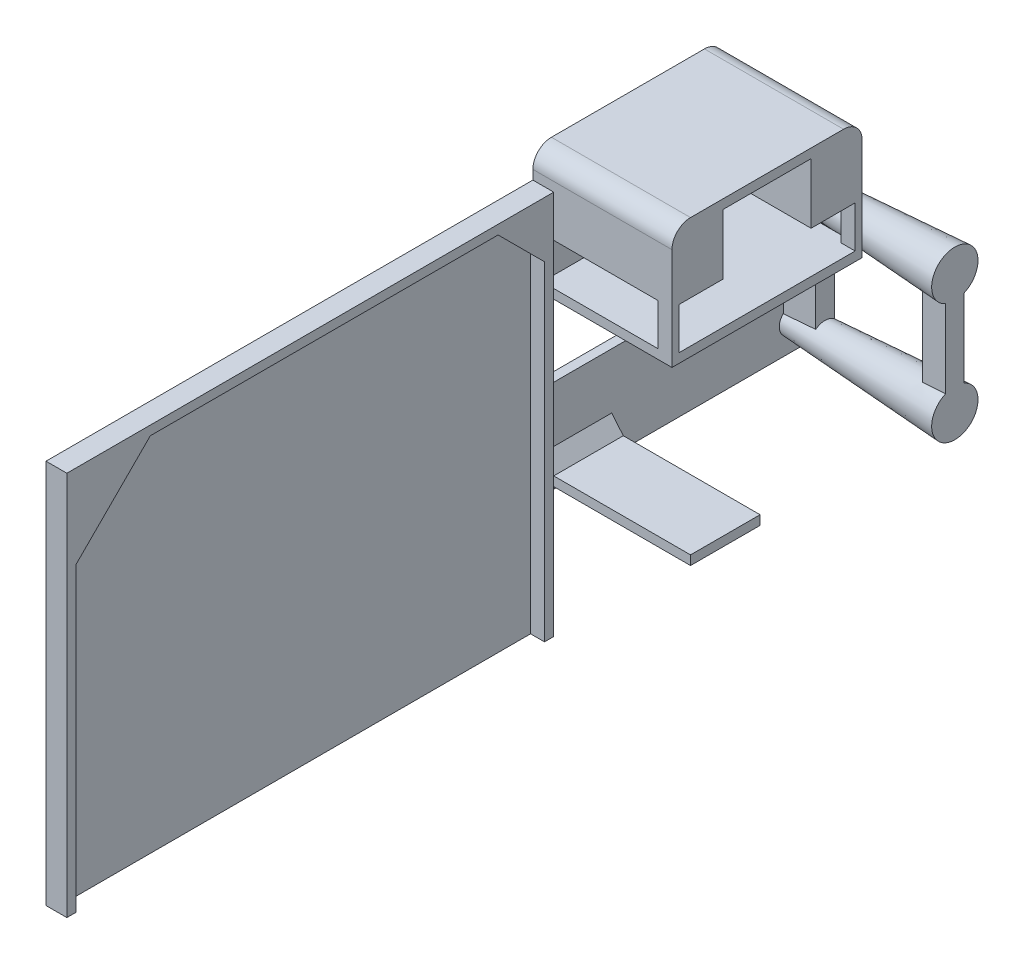
SolidWorks part; units mm, degrees
ref_plane "Front Plane" through (0, 0, 0) normal (0, 0, 1) x (1, 0, 0)
ref_plane "Top Plane" through (0, 0, 0) normal (0, 1, 0) x (1, 0, 0)
ref_plane "Right Plane" through (0, 0, 0) normal (1, 0, 0) x (0, 0, -1)
sketch "Sketch6" plane through (0, 0, 0) normal (1, 0, 0) x (0, 0, -1)
  line L1 (0, 0) -> (105, 0)
  line L2 (0, 0) -> (0, -83)
  line L3 (0, -83) -> (105, -83)
  line L4 (105, 0) -> (105, -83)
  dimension "D1" = 105
  dimension "D2" = 83
extrude "Boss-Extrude3" add sketch "Sketch6" along normal blind 4.5
sketch "Sketch9" plane through (0, -83, 0) normal (0, -1, 0) x (1, 0, 0)
  line L0 (4.5, 0) -> (4.5, -105) construction
  line L1 (0, 0) -> (0, -105) construction
  line L2 (4.5, -2) -> (1.5, -2)
  line L3 (4.5, -2) -> (4.5, -103)
  line L4 (4.5, -103) -> (1.5, -103)
  line L5 (1.5, -2) -> (1.5, -103)
  line L6 (4.5, 0) -> (0, 0) construction
  line L7 (4.5, -105) -> (0, -105) construction
  dimension "D1" = 1.5
  dimension "D2" = 2
  dimension "D3" = 2
extrude "Cut-Extrude6" cut sketch "Sketch9" against normal blind 81
sketch "Sketch10" plane through (0, 0, -2) normal (0, 0, -1) x (-1, 0, 0)
  line L1 (-4.5, -2) -> (-3.5, -2)
  line L2 (-4.5, -2) -> (-4.5, -10)
  line L3 (-4.5, -10) -> (-3.5, -10)
  line L4 (-3.5, -2) -> (-3.5, -10)
  dimension "D1" = 1
  dimension "D2" = 8
extrude "Boss-Extrude4" add sketch "Sketch10" along normal blind 8
sketch "Sketch11" plane through (0, 0, -103) normal (0, 0, 1) x (1, 0, 0)
  line L1 (4.5, -2) -> (3.2738, -2)
  line L2 (4.5, -2) -> (4.5, -7)
  line L3 (4.5, -7) -> (3.2738, -7)
  line L4 (3.2738, -2) -> (3.2738, -7)
  dimension "D1" = 5
extrude "Boss-Extrude5" add sketch "Sketch11" along normal blind 5
sketch "Sketch18" plane through (4.5, 0, 0) normal (1, 0, 0) x (0, 0, -1)
  line L0 (103, -12) -> (93, -2)
  line L1 (103, -7) -> (103, -83) construction
  line L2 (98, -2) -> (10, -2) construction
  line L3 (103, -12) -> (103, -2)
  line L4 (103, -2) -> (93, -2)
  line L5 (18, -2) -> (2, -2)
  line L6 (2, -2) -> (2, -18)
  line L7 (2, -10) -> (2, -83) construction
  line L8 (2, -18) -> (18, -2)
  dimension "D1" = 0
  dimension "D2" = 10
  dimension "D3" = 0
  dimension "D4" = 16
  dimension "D5" = 22.6274
extrude "Boss-Extrude12" add sketch "Sketch18" against normal up to vertex (1.2262 mm away)
sketch "Sketch27" plane through (0, 0, 0) normal (-1, 0, 0) x (0, 0, 1)
  line L0 (-105, -83) -> (-105, 0) construction
  line L1 (-105, -55) -> (-120, -55)
  line L2 (-105, -55) -> (-105, -53)
  line L3 (-105, -53) -> (-120, -53)
  line L4 (-120, -55) -> (-120, -53)
  line L5 (-125.5, -18) -> (-125.5, 21.7068) construction
  line L6 (-105, -20) -> (-146, -20)
  line L7 (-105, -20) -> (-105, -18)
  line L8 (-105, -18) -> (-146, -18)
  line L9 (-146, -20) -> (-146, -18)
  line L10 (-105, -9) -> (-116, -9)
  line L11 (-105, -9) -> (-105, 6)
  line L12 (-105, 6) -> (-116, 6)
  line L13 (-116, -9) -> (-116, 6)
  line L14 (-146, 6) -> (-135, 6)
  line L15 (-135, -9) -> (-135, 6)
  line L16 (-146, -9) -> (-135, -9)
  line L17 (-146, -9) -> (-146, 6)
  dimension "D1" = 15
  dimension "D2" = 28
  dimension "D3" = 63
  dimension "D4" = 41
  dimension "D5" = 2
  dimension "D6" = 2
  dimension "D7" = 9
  dimension "D8" = 15
  dimension "D9" = 11
extrude "Boss-Extrude20" add sketch "Sketch27" against normal blind 30
sketch "Sketch28" plane through (30, 0, 0) normal (1, 0, 0) x (0, 0, -1)
  line L0 (146, -9) -> (135, -9) construction
  line L1 (146, -20) -> (144.5, -20)
  line L2 (146, -20) -> (146, -9)
  line L3 (146, -9) -> (144.5, -9)
  line L4 (144.5, -20) -> (144.5, -9)
  line L5 (125.5, -18) -> (125.5, -4.7212) construction
  line L6 (105, -18) -> (146, -18) construction
  line L7 (105, -9) -> (106.5, -9)
  line L8 (106.5, -20) -> (106.5, -9)
  line L9 (105, -20) -> (106.5, -20)
  line L10 (105, -20) -> (105, -9)
  dimension "D1" = 1.5
extrude "Boss-Extrude21" add sketch "Sketch28" against normal blind 3
sketch "Sketch29" plane through (30, 0, 0) normal (1, 0, 0) x (0, 0, -1)
  line L0 (105, -20) -> (105, 6) construction
  line L1 (146, 6) -> (105, 6)
  line L2 (146, 6) -> (146, 4)
  line L3 (146, 4) -> (105, 4)
  line L4 (105, 6) -> (105, 4)
  dimension "D1" = 2
extrude "Boss-Extrude22" add sketch "Sketch29" against normal up to vertex (30 mm away)
sketch "Sketch30" plane through (0, 0, -105) normal (0, 0, -1) x (-1, 0, 0)
  line L0 (0, -83) -> (0, -55) construction
  line L1 (0, -58) -> (-2, -58)
  line L2 (0, -58) -> (0, -20)
  line L3 (0, -20) -> (-2, -20)
  line L4 (-2, -58) -> (-2, -20)
  dimension "D1" = 2
  dimension "D2" = 25
  dimension "D3" = 0
extrude "Boss-Extrude23" add sketch "Sketch30" along normal blind 60
sketch "Sketch31" plane through (2, 0, 0) normal (1, 0, 0) x (0, 0, -1)
  line L0 (165, -58) -> (105, -58) construction
  line L1 (165, -20) -> (165, -58) construction
  line L2 (165, -39) -> (129.1416, -39) construction
  circle A0 centre (159, -52) radius 5
  circle A1 centre (159, -26) radius 5
  dimension "D1" = 10
  dimension "D2" = 6
  dimension "D3" = 6
extrude "Boss-Extrude24" add sketch "Sketch31" along normal blind 35
draft "Draft1" type of draft neutral plane draft angle 3.5 faces to draft 1 face at (37, -52, -164) neutral plane through (37, -52, -159) neutral plane normal (1, 0, 0) reverse direction yes parameters "D1"=3.5
draft "Draft3" type of draft neutral plane draft angle 3.5 faces to draft 1 face at (37, -26, -154) neutral plane through (37, -26, -159) neutral plane normal (1, 0, 0) reverse direction yes parameters "D1"=3.5
sketch "Sketch32" plane through (2, 0, 0) normal (1, 0, 0) x (0, 0, -1)
  line L1 (161, -53) -> (157, -53)
  line L2 (161, -53) -> (161, -25)
  line L3 (161, -25) -> (157, -25)
  line L4 (157, -53) -> (157, -25)
  circle A0 centre (159, -52) radius 2.8593 construction
  circle A1 centre (159, -26) radius 2.8593 construction
  dimension "D1" = 2
  dimension "D2" = 2
  dimension "D3" = 1
  dimension "D4" = 1
  dimension "D5" = 2
extrude "Boss-Extrude25" add sketch "Sketch32" along normal blind 7
sketch "Sketch33" plane through (37, 0, 0) normal (1, 0, 0) x (0, 0, -1)
  line L1 (157, -26) -> (161, -26)
  line L2 (157, -26) -> (157, -52)
  line L3 (157, -52) -> (161, -52)
  line L4 (161, -26) -> (161, -52)
  circle A0 centre (159, -26) radius 5 construction
  circle A1 centre (159, -52) radius 5 construction
  point P6 (159, -26)
  dimension "D1" = 0
  dimension "D2" = 4
  dimension "D3" = 0
  dimension "D4" = 0
extrude "Boss-Extrude26" add sketch "Sketch33" against normal blind 5
sketch "Sketch39" plane through (0, 0, 0) normal (-1, 0, 0) x (0, 0, 1)
  line L0 (-105, -18) -> (-105, -9) construction
  line L1 (-146, 6) -> (-105, 6)
  line L2 (-146, 6) -> (-146, -18)
  line L3 (-146, -18) -> (-105, -18)
  line L4 (-105, 6) -> (-105, -18)
  line L5 (-105, -18) -> (-146, -18) construction
  dimension "D1" = 0
  dimension "D2" = 0
extrude "Boss-Extrude30" add sketch "Sketch39" against normal blind 2
sketch "Sketch40" plane through (2, 0, 0) normal (1, 0, 0) x (0, 0, -1)
  line L1 (116, 4) -> (135, 4) construction
  line L2 (116, -9) -> (116, 4) construction
  circle A0 centre (125.5, -6.5) radius 5
  point P4 (125.5, 4)
  point P7 (116, -2.5)
  dimension "D1" = 0
  dimension "D2" = 4
  dimension "D3" = 10
extrude "Cut-Extrude9" cut sketch "Sketch40" against normal blind 2
sketch "Sketch41" plane through (0, 0, -120) normal (0, 0, -1) x (-1, 0, 0)
  line L0 (-2, -54) -> (-7.9406, -54) construction
  line L1 (-2, -55) -> (-2, -53) construction
  line L2 (-2, -55) -> (-2, -58)
  line L3 (-2, -58) -> (-4.5, -55)
  line L4 (-30, -55) -> (-2, -55) construction
  line L5 (-4.5, -55) -> (-2, -55)
  line L7 (-2, -50) -> (-4.5, -53)
  line L8 (-2, -53) -> (-2, -50)
  line L9 (-4.5, -53) -> (-2, -53)
  dimension "D1" = 0
  dimension "D2" = 0
extrude "Boss-Extrude31" add sketch "Sketch41" along direction (0, 0, 1) on the side against the normal up to surface (15 mm away)
sketch "Sketch42" plane through (30, 0, 0) normal (1, 0, 0) x (0, 0, -1)
  line L1 (105, -55) -> (120, -55)
  line L2 (105, -55) -> (105, -53)
  line L3 (105, -53) -> (120, -53)
  line L4 (120, -55) -> (120, -53)
extrude "Boss-Extrude32" add sketch "Sketch42" along normal blind 4
sketch "Sketch45" plane through (2, 0, 0) normal (1, 0, 0) x (0, 0, -1)
  line L0 (165, -58) -> (120, -58) construction
  line L1 (105, -20) -> (135, -20)
  line L2 (105, -20) -> (105, -38)
  line L3 (105, -38) -> (135, -38)
  line L4 (135, -20) -> (135, -38)
  line L5 (165, -20) -> (165, -58) construction
  dimension "D1" = 20
  dimension "D2" = 30
extrude "Cut-Extrude10" cut sketch "Sketch45" against normal blind 5
fillet "Fillet1" radius 4 1 edges at (15, 6, -146)
fillet "Fillet2" radius 4 1 edges at (15, 6, -105)
